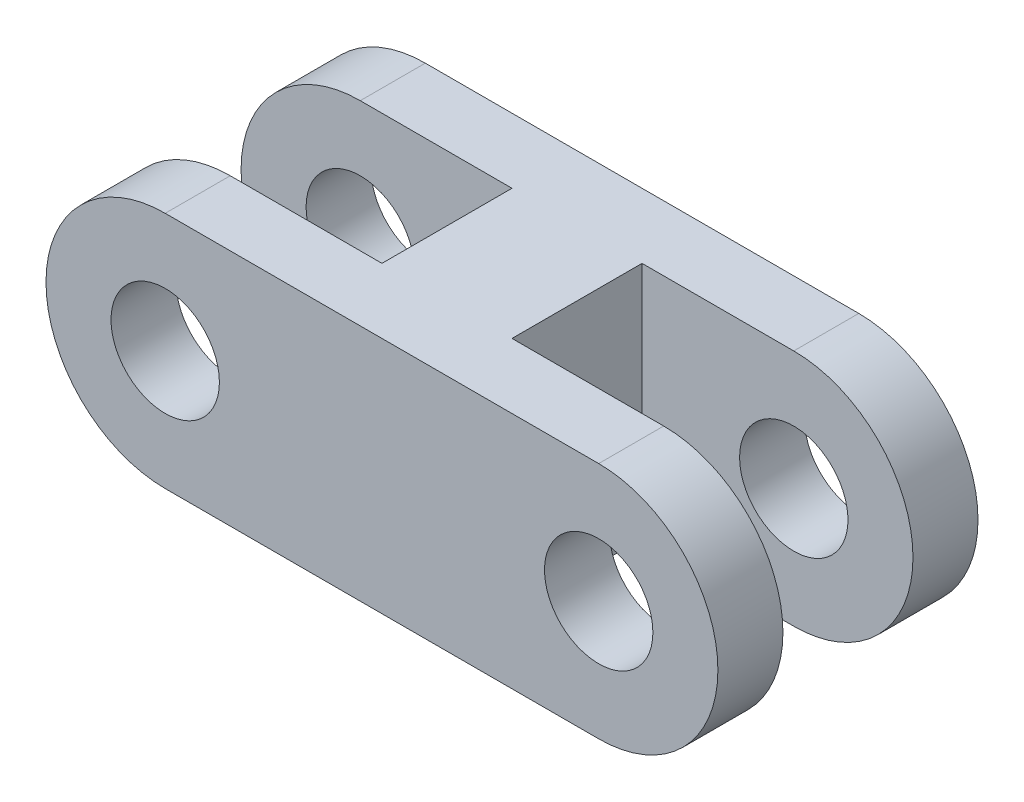
SolidWorks part; units mm, degrees
ref_plane "Front" through (0, 0, 0) normal (0, 0, 1) x (1, 0, 0)
ref_plane "Top" through (0, 0, 0) normal (0, 1, 0) x (1, 0, 0)
ref_plane "Right" through (0, 0, 0) normal (1, 0, 0) x (0, 0, -1)
sketch "Sketch5" plane through (0, 0, 0) normal (0, 0, 1) x (1, 0, 0)
  line L0 (0, 0) -> (20, 0) construction
  line L1 (0, 5.5) -> (20, 5.5)
  line L2 (0, -5.5) -> (20, -5.5)
  arc A0 (0, 5.5) -> (0, -5.5) centre (0, 0) ccw
  arc A1 (20, -5.5) -> (20, 5.5) centre (20, 0) ccw
  point P3 (10, 0)
  dimension "D1" = 20
  dimension "D2" = 11
extrude "Boss-Extrude1" add sketch "Sketch5" along normal blind 12
sketch "Sketch6" plane through (0, 5.5, 0) normal (0, 1, 0) x (1, 0, 0)
  line L0 (-5.5, 0) -> (-5.5, -12) construction
  line L1 (-5.5, -3) -> (7, -3)
  line L2 (-5.5, -3) -> (-5.5, -9)
  line L3 (-5.5, -9) -> (7, -9)
  line L4 (7, -3) -> (7, -9)
  line L5 (25.5, -12) -> (25.5, 0) construction
  line L6 (25.5, -3) -> (13, -3)
  line L7 (25.5, -3) -> (25.5, -9)
  line L8 (25.5, -9) -> (13, -9)
  line L9 (13, -3) -> (13, -9)
  line L10 (0, 0) -> (-5.5, 0) construction
  dimension "D1" = 7
  dimension "D2" = 3
  dimension "D3" = 6
sketch "Sketch2" plane through (0, 0, 0) normal (0, 0, 1) x (1, 0, 0)
  circle A0 centre (0, 0) radius 2.5
  circle A1 centre (20, 0) radius 2.5
  dimension "D1" = 5
extrude "Cut-Extrude1" cut sketch "Sketch6" against normal through all
extrude "Cut-Extrude2" cut sketch "Sketch2" along normal through all
